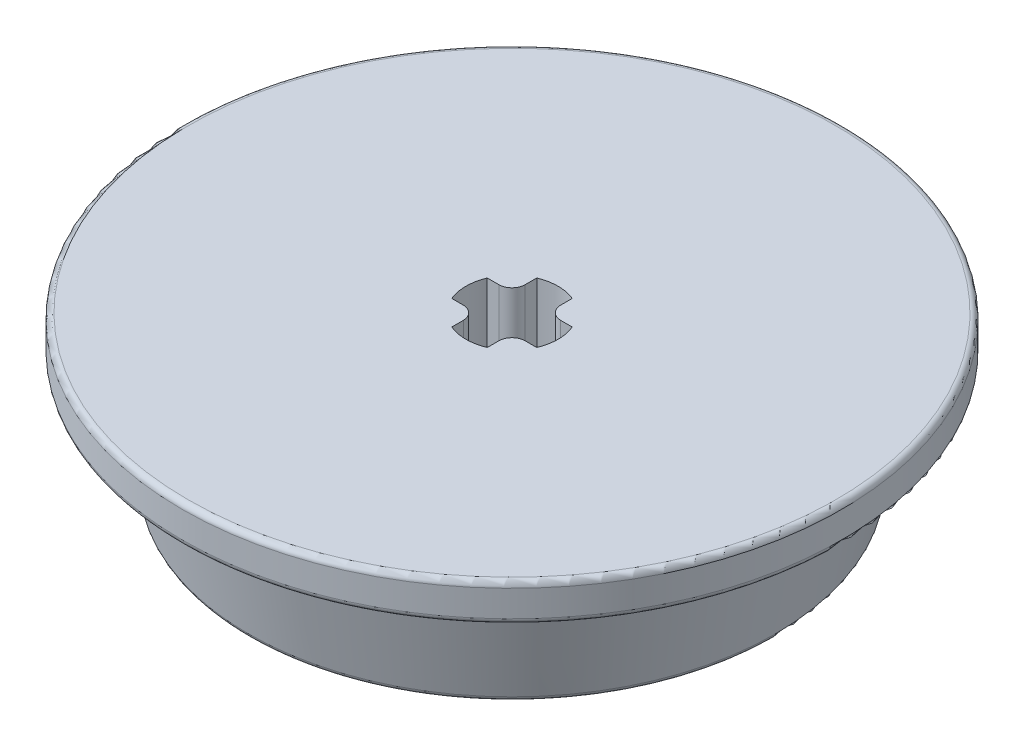
SolidWorks part; units mm, degrees
ref_plane "Front Plane" through (0, 0, 0) normal (0, 0, 1) x (1, 0, 0)
ref_plane "Top Plane" through (0, 0, 0) normal (0, 1, 0) x (1, 0, 0)
ref_plane "Right Plane" through (0, 0, 0) normal (1, 0, 0) x (0, 0, -1)
sketch "Sketch1" plane through (0, 0, 0) normal (0, 1, 0) x (1, 0, 0)
  line L2 (0, 0) -> (0, 47.5777) construction
  line L3 (0, 0) -> (50000, 0) construction
  line L6 (-0.89, 0.89) -> (0, 0) construction
  line L7 (0, 0) -> (0.89, 0.89) construction
  line L12 (2.39, 0) -> (2.39, 3.5727) construction
  line L13 (0, 2.39) -> (50000, 2.39) construction
  line L14 (-2.39, 0.4111) -> (-2.39, -49999.5889) construction
  line L15 (0.2318, -2.39) -> (-49999.7682, -2.39) construction
  line L16 (0, 0) -> (-0.89, -0.89) construction
  line L17 (0, 0) -> (0.89, -0.89) construction
  line L18 (-0.94, 0.94) -> (-2.2517, 0.94)
  line L19 (-2.2517, -0.94) -> (-0.94, -0.94)
  line L20 (-0.94, -0.94) -> (-0.94, -2.2517)
  line L21 (0.94, -2.2517) -> (0.94, -0.94)
  line L22 (0.94, -0.94) -> (2.2517, -0.94)
  line L23 (0.94, 0.94) -> (2.2517, 0.94)
  line L24 (0.94, 2.2517) -> (0.94, 0.94)
  line L25 (-0.94, 2.2517) -> (-0.94, 0.94)
  arc A4 (-2.2517, 0.94) -> (-2.2517, -0.94) centre (0, 0) ccw
  arc A5 (-0.94, -2.2517) -> (0.94, -2.2517) centre (0, 0) ccw
  arc A6 (2.2517, 0.94) -> (2.2517, -0.94) centre (0, 0) cw
  arc A7 (-0.94, 2.2517) -> (0.94, 2.2517) centre (0, 0) cw
  point P15 (0, 2.39)
  point P24 (2.39, 0)
  point P29 (-2.39, 0)
  point P30 (0, -2.39)
  line B0 (-0.89, 2.2181) -> (-0.89, 0.89) construction
  line B1 (-0.89, 0.89) -> (-2.2181, 0.89) construction
  line B2 (0.89, 2.2181) -> (0.89, 0.89) construction
  line B3 (0.89, 0.89) -> (2.2181, 0.89) construction
  line B4 (-2.2181, -0.89) -> (-0.89, -0.89) construction
  line B5 (-0.89, -0.89) -> (-0.89, -2.2181) construction
  line B6 (0.89, -2.2181) -> (0.89, -0.89) construction
  line B7 (0.89, -0.89) -> (2.2181, -0.89) construction
  arc B8 (-0.89, 2.2181) -> (0.89, 2.2181) centre (0, 0) cw construction
  arc B9 (-2.2181, 0.89) -> (-2.2181, -0.89) centre (0, 0) ccw construction
  arc B10 (2.2181, 0.89) -> (2.2181, -0.89) centre (0, 0) cw construction
  arc B11 (-0.89, -2.2181) -> (0.89, -2.2181) centre (0, 0) ccw construction
  dimension "D1" = 45
  dimension "D2" = 45
  dimension "D3" = 4.78
  dimension "D4" = 45
  dimension "D5" = 4.78
  dimension "D6" = 1.5
sketch_block_instance "Lego Axle - Unfilleted-1"
sketch_block "Lego Axle - Unfilleted" parameters "D1"=10.5762, "D2"=12.3972, "D3"=62.5785, "D4"=1.2287, "D5"=12.9019, "D6"=1.0841, "D7"=0.05
sketch "Sketch2" plane through (0, 0, 0) normal (0, 0, 1) x (1, 0, 0)
  line L0 (0, 0) -> (17.4605, 0)
  line L1 (200000.2318, 0) -> (-249999.7682, 0) construction
  line L2 (17.4605, 0) -> (17.4605, -2)
  line L3 (17.4605, -2) -> (15, -2)
  line L4 (15, -2) -> (13.9155, -8)
  line L5 (13.9155, -8) -> (0, -8)
  line L6 (0, -8) -> (0, 0)
  line L7 (0, 0) -> (0, 50000) construction
  dimension "D1" = 30
  dimension "D2" = 27.831
  dimension "D3" = 8
  dimension "D4" = 2
revolve "Revolve1" add sketch "Sketch2" angle 360 about L7
extrude "Cut-Extrude1" cut sketch "Sketch1" against normal through all
fillet "Fillet1" radius 0.7 4 edges at (-0.94, -4, 0.94) (0.94, -4, 0.94) (0.94, -4, -0.94) (-0.94, -4, -0.94)
fillet "Fillet2" radius 0.3 4 edges at (0, -8, -13.9155) (0, 0, -17.4605) (0, -2, -15) (0, -2, -17.4605)
equation "\"D2@Sketch2\"=0.9277*\"D1@Sketch2\""
